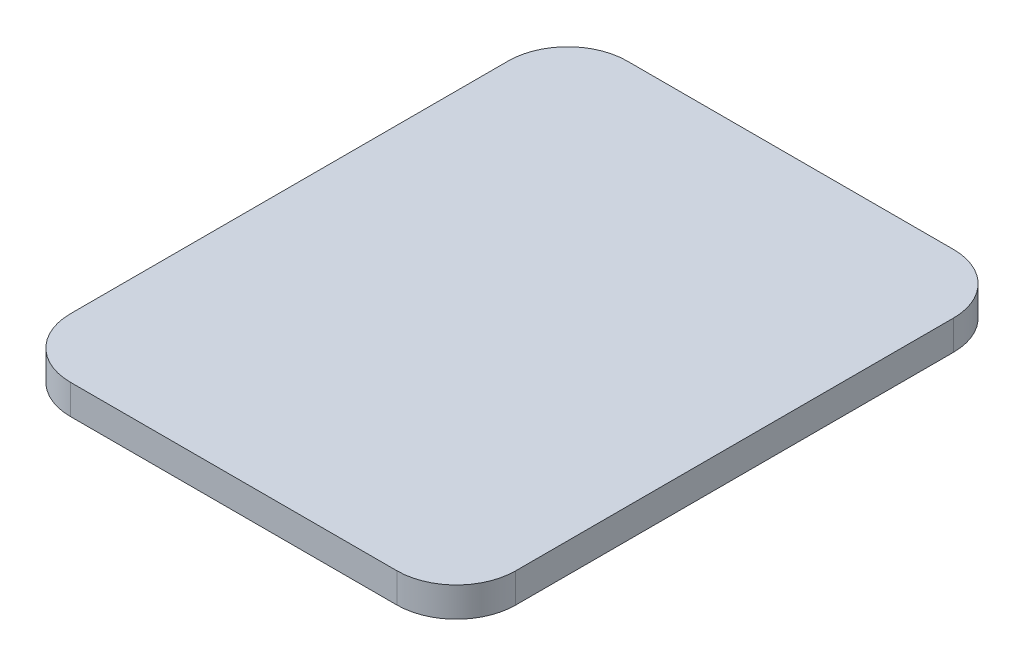
SolidWorks part; units mm, degrees
material "Кремний"
ref_plane "Спереди" through (0, 0, 0) normal (0, 0, 1) x (1, 0, 0)
ref_plane "Сверху" through (0, 0, 0) normal (0, 1, 0) x (1, 0, 0)
ref_plane "Справа" through (0, 0, 0) normal (1, 0, 0) x (0, 0, -1)
sketch "Эскиз экрана" plane through (0, 0, 0) normal (0, 1, 0) x (1, 0, 0)
  line L1 (-11, 18.75) -> (11, 18.75)
  line L2 (-15, 14.75) -> (-15, -14.75)
  line L3 (-11, -18.75) -> (11, -18.75)
  line L4 (15, 14.75) -> (15, -14.75)
  arc A0 (-15, -14.75) -> (-11, -18.75) centre (-11, -14.75) ccw
  arc A1 (11, -18.75) -> (15, -14.75) centre (11, -14.75) ccw
  arc A2 (11, 18.75) -> (15, 14.75) centre (11, 14.75) cw
  arc A3 (-11, 18.75) -> (-15, 14.75) centre (-11, 14.75) ccw
  point P7 (-15, -18.75)
  point P12 (15, 18.75)
  point P15 (-15, 18.75)
  dimension "D5" = 4
  dimension "D1" = 37.5
  dimension "D2" = 30
  dimension "D3" = 15
  dimension "D4" = 18.75
extrude "Экран" add sketch "Эскиз экрана" against normal blind 2
